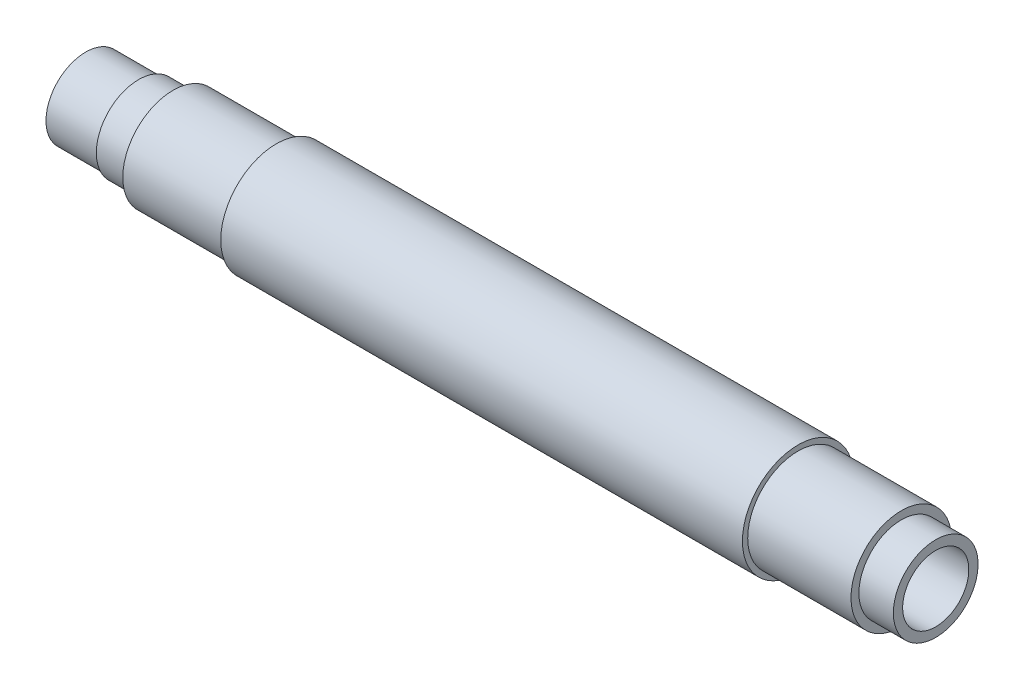
SolidWorks part; units mm, degrees
ref_plane "前视基准面" through (0, 0, 0) normal (0, 0, 1) x (1, 0, 0)
ref_plane "上视基准面" through (0, 0, 0) normal (0, 1, 0) x (1, 0, 0)
ref_plane "右视基准面" through (0, 0, 0) normal (1, 0, 0) x (0, 0, -1)
sketch "Sketch1" plane through (0, 0, 0) normal (0, 0, 1) x (1, 0, 0)
  line L0 (0, 0) -> (124.963, 0) construction
  line L1 (0, 21) -> (-98.5, 21)
  line L2 (-98.5, 21) -> (-98.5, 19)
  line L3 (-98.5, 19) -> (-137.5, 19)
  line L7 (-137.5, 19) -> (-137.5, 16)
  line L8 (-137.5, 16) -> (-150.5, 16)
  line L13 (-170.5, 12.5) -> (0, 12.5)
  line L14 (0, 12.5) -> (0, 21)
  line L16 (-150.5, 16) -> (-150.5, 15)
  line L17 (-150.5, 15) -> (-170.5, 15)
  line L18 (-170.5, 15) -> (-170.5, 12.5)
  dimension "D1" = 42
  dimension "D2" = 38
  dimension "D3" = 98.5
  dimension "D4" = 13
  dimension "D5" = 3
  dimension "D6" = 39
  dimension "D7" = 30
  dimension "D8" = 25
  dimension "D9" = 20
revolve "Revolve1" add sketch "Sketch1" angle 360 about L0
cosmetic thread "Cosmetic Thread1" parameters "D2"=15.294
mirror "Mirror1" about plane through (0, 0, 0) normal (1, 0, 0) of "Revolve1"
sketch "Sketch2" plane through (170.5, 0, 0) normal (1, 0, 0) x (0, 0, -1)
  circle A1 centre (0, 0) radius 15
  circle A2 centre (0, 0) radius 15
  dimension "D1" = 0
extrude "Extrude1" cut sketch "Sketch2" against normal up to surface (20 mm away) up to face at (150.5, 0, 15)
